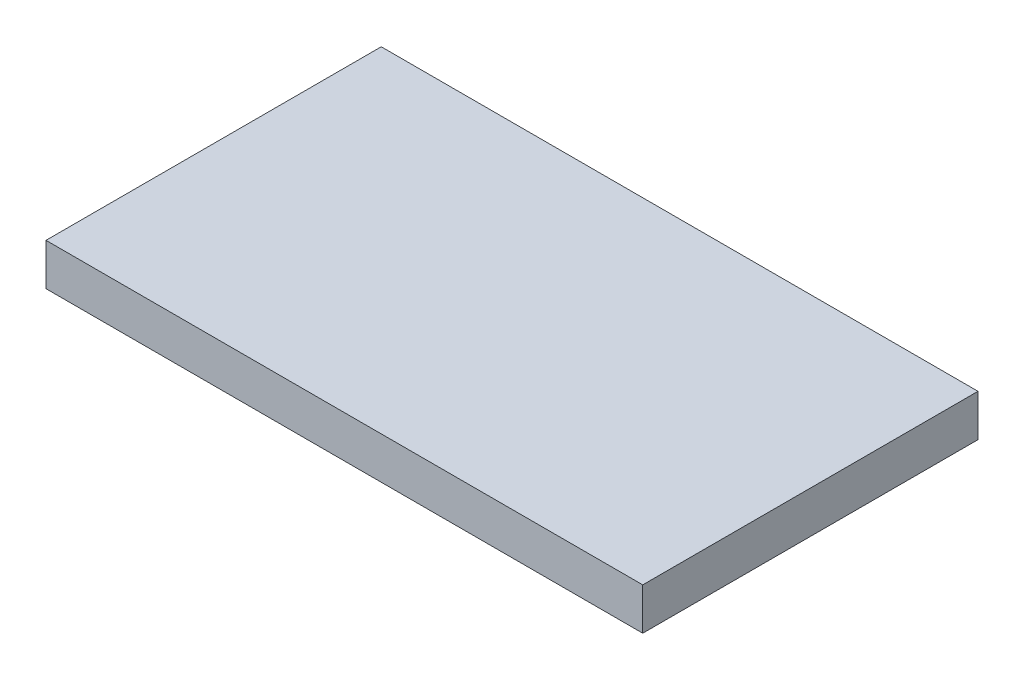
SolidWorks part; units mm, degrees
ref_plane "Front Plane" through (0, 0, 0) normal (0, 0, 1) x (1, 0, 0)
ref_plane "Top Plane" through (0, 0, 0) normal (0, 1, 0) x (1, 0, 0)
ref_plane "Right Plane" through (0, 0, 0) normal (1, 0, 0) x (0, 0, -1)
sketch "Sketch1" plane through (0, 0, 0) normal (0, 1, 0) x (1, 0, 0)
  line L1 (-8.9, 5) -> (8.9, 5)
  line L2 (-8.9, 5) -> (-8.9, -5)
  line L3 (-8.9, -5) -> (8.9, -5)
  line L4 (8.9, 5) -> (8.9, -5)
  line L5 (-8.9, 5) -> (8.9, -5) construction
  line L6 (-8.9, -5) -> (8.9, 5) construction
  point P0 (0, 0)
  dimension "D1" = 10
  dimension "D2" = 17.8
extrude "Boss-Extrude1" add sketch "Sketch1" along normal blind 1.25
